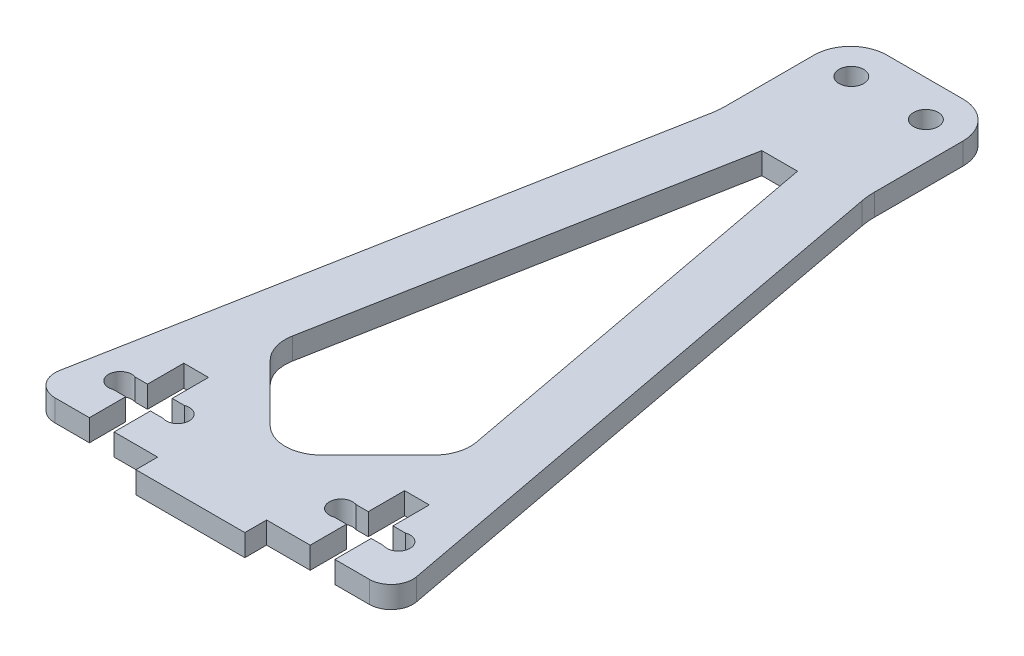
SolidWorks part; units mm, degrees
material "Thornel Mat VMA"
ref_plane "前视基准面" through (0, 0, 0) normal (0, 0, 1) x (1, 0, 0)
ref_plane "上视基准面" through (0, 0, 0) normal (0, 1, 0) x (1, 0, 0)
ref_plane "右视基准面" through (0, 0, 0) normal (1, 0, 0) x (0, 0, -1)
sketch "草图1" plane through (0, 0, 0) normal (0, 1, 0) x (1, 0, 0)
  line L1 (-10.25, 49.07) -> (10.25, 49.07)
  line L2 (-10.25, 49.07) -> (-10.25, -49.07)
  line L3 (-10.25, -49.07) -> (10.25, -49.07)
  line L4 (10.25, 49.07) -> (10.25, -49.07)
  line L5 (-10.25, 49.07) -> (10.25, -49.07) construction
  line L6 (-10.25, -49.07) -> (10.25, 49.07) construction
  circle A0 centre (-5.135, 44.07) radius 1.7
  circle A1 centre (5.135, 44.07) radius 1.7
  point P0 (0, 0)
  dimension "D2" = 10.27
  dimension "D3" = 3.4
  dimension "D4" = 3.4
  dimension "D5" = 5
  dimension "D6" = 5
  dimension "D7" = 5.115
  dimension "D1" = 20.5
  dimension "D8" = 98.14
extrude "凸台-拉伸1" add sketch "草图1" along normal blind 3
fillet "圆角1" radius 5 2 edges at (10.25, 1.5, -49.07) (-10.25, 1.5, -49.07)
sketch "草图2" plane through (0, 3, 0) normal (0, 1, 0) x (1, 0, 0)
  line L0 (-10.25, 30.93) -> (-25.25, -49.07)
  line L1 (-10.25, 44.07) -> (-10.25, -49.07) construction
  line L2 (-25.25, -49.07) -> (-10.25, -49.07)
  line L3 (-10.25, -49.07) -> (-10.25, 30.93)
  line L4 (10.25, 30.93) -> (10.25, -49.07)
  line L5 (10.25, -49.07) -> (10.25, 44.07) construction
  line L6 (10.25, -49.07) -> (25.25, -49.07)
  line L7 (25.25, -49.07) -> (10.25, 30.93)
  dimension "D1" = 15
  dimension "D2" = 15
  dimension "D3" = 80
  dimension "D4" = 80
extrude "凸台-拉伸2" add sketch "草图2" against normal up to surface (3 mm away) up to face at (0, 0, -15.0352)
fillet "圆角2" radius 10 2 edges at (-10.25, 1.5, -30.93) (10.25, 1.5, -30.93)
sketch "草图3" plane through (0, 3, 0) normal (0, 1, 0) x (1, 0, 0)
  line L9 (-7.5, -49.07) -> (-7.5, -52.07)
  line L10 (-25.25, -49.07) -> (25.25, -49.07) construction
  line L11 (-7.5, -52.07) -> (7.5, -52.07)
  line L12 (7.5, -52.07) -> (7.5, -49.07)
  line L13 (7.5, -49.07) -> (-7.5, -49.07)
  dimension "D1" = 15
  dimension "D2" = 17.75
  dimension "D3" = 3
extrude "凸台-拉伸3" add sketch "草图3" against normal up to surface (3 mm away) up to face at (0, 0, -21.3955)
sketch "草图5" plane through (0, 3, 0) normal (0, 1, 0) x (1, 0, 0)
  line L0 (-16.9, -49.07) -> (-16.9, -44.07)
  line L1 (-25.25, -49.07) -> (-7.5, -49.07) construction
  line L2 (-16.9, -44.07) -> (-18.6, -44.07)
  line L3 (-18.6, -44.07) -> (-18.6, -41.07)
  line L4 (-18.6, -41.07) -> (-16.9, -41.07)
  line L5 (-16.9, -41.07) -> (-16.9, -36.07)
  line L6 (-16.9, -36.07) -> (-13.5, -36.07)
  line L7 (-13.5, -36.07) -> (-13.5, -41.07)
  line L8 (-13.5, -41.07) -> (-11.8, -41.07)
  line L9 (-11.8, -41.07) -> (-11.8, -44.07)
  line L10 (-11.8, -44.07) -> (-13.5, -44.07)
  line L11 (-13.5, -44.07) -> (-13.5, -49.07)
  line L12 (-13.5, -49.07) -> (-16.9, -49.07)
  line L13 (0, -52.07) -> (0, -45.4738) construction
  line L14 (-7.5, -52.07) -> (7.5, -52.07) construction
  line L15 (-7.5, -49.07) -> (-7.5, -52.07) construction
  line L17 (13.5, -49.07) -> (16.9, -49.07)
  line L18 (13.5, -44.07) -> (13.5, -49.07)
  line L19 (11.8, -44.07) -> (13.5, -44.07)
  line L20 (11.8, -41.07) -> (11.8, -44.07)
  line L21 (13.5, -41.07) -> (11.8, -41.07)
  line L22 (13.5, -36.07) -> (13.5, -41.07)
  line L23 (16.9, -36.07) -> (13.5, -36.07)
  line L24 (16.9, -41.07) -> (16.9, -36.07)
  line L25 (18.6, -41.07) -> (16.9, -41.07)
  line L26 (18.6, -44.07) -> (18.6, -41.07)
  line L27 (16.9, -44.07) -> (18.6, -44.07)
  line L28 (16.9, -49.07) -> (16.9, -44.07)
  dimension "D1" = 5
  dimension "D2" = 5
  dimension "D3" = 5
  dimension "D4" = 5
  dimension "D5" = 1.7
  dimension "D6" = 1.7
  dimension "D7" = 1.7
  dimension "D8" = 3.4
  dimension "D9" = 3.4
  dimension "D10" = 3
  dimension "D11" = 6
extrude "切除-拉伸1" cut sketch "草图5" against normal blind 10
sketch "草图6" plane through (0, 3, 0) normal (0, 1, 0) x (1, 0, 0)
  line L0 (-2.4593, 29.07) -> (2.4593, 29.07)
  line L1 (2.4593, 29.07) -> (13.1481, -27.9366)
  line L2 (13.1481, -27.9366) -> (0, -41.0847)
  line L4 (0, -41.0847) -> (-13.1481, -27.9366)
  line L5 (-13.1481, -27.9366) -> (-2.4593, 29.07)
  line L6 (-10.4213, 30.0165) -> (-25.25, -49.07) construction
  line L7 (25.25, -49.07) -> (10.4213, 30.0165) construction
  line L8 (0, -52.07) -> (0, -47.435) construction
  line L9 (-7.5, -52.07) -> (7.5, -52.07) construction
  line L10 (5.25, 49.07) -> (-5.25, 49.07) construction
  dimension "D1" = 8
  dimension "D2" = 8
  dimension "D3" = 6
  dimension "D4" = 6
  dimension "D5" = 90
  dimension "D6" = 20
extrude "切除-拉伸2" cut sketch "草图6" against normal blind 10
fillet "圆角3" radius 5 3 edges at (-13.1481, 1.5, 27.9366) (13.1481, 1.5, 27.9366) (0, 1.5, 41.0847)
fillet "圆角4" radius 3 2 edges at (25.25, 1.5, 49.07) (-25.25, 1.5, 49.07)
sketch "草图7" plane through (0, 0, 0) normal (0, -1, 0) x (1, 0, 0)
  line L2 (-18.6, 44.07) -> (-18.6, 41.07)
  line L3 (-11.8, 44.07) -> (-11.8, 41.07)
  line L4 (11.8, 44.07) -> (11.8, 41.07)
  line L5 (18.6, 44.07) -> (18.6, 41.07)
  arc A0 (-11.8, 41.07) -> (-11.8, 44.07) centre (-11.2432, 42.57) ccw
  arc A1 (-18.6, 44.07) -> (-18.6, 41.07) centre (-19.1568, 42.57) ccw
  arc A2 (18.6, 41.07) -> (18.6, 44.07) centre (19.1568, 42.57) ccw
  arc A3 (11.8, 44.07) -> (11.8, 41.07) centre (11.2432, 42.57) ccw
  dimension "D1" = 3.2
extrude "切除-拉伸3" cut sketch "草图7" against normal blind 10
